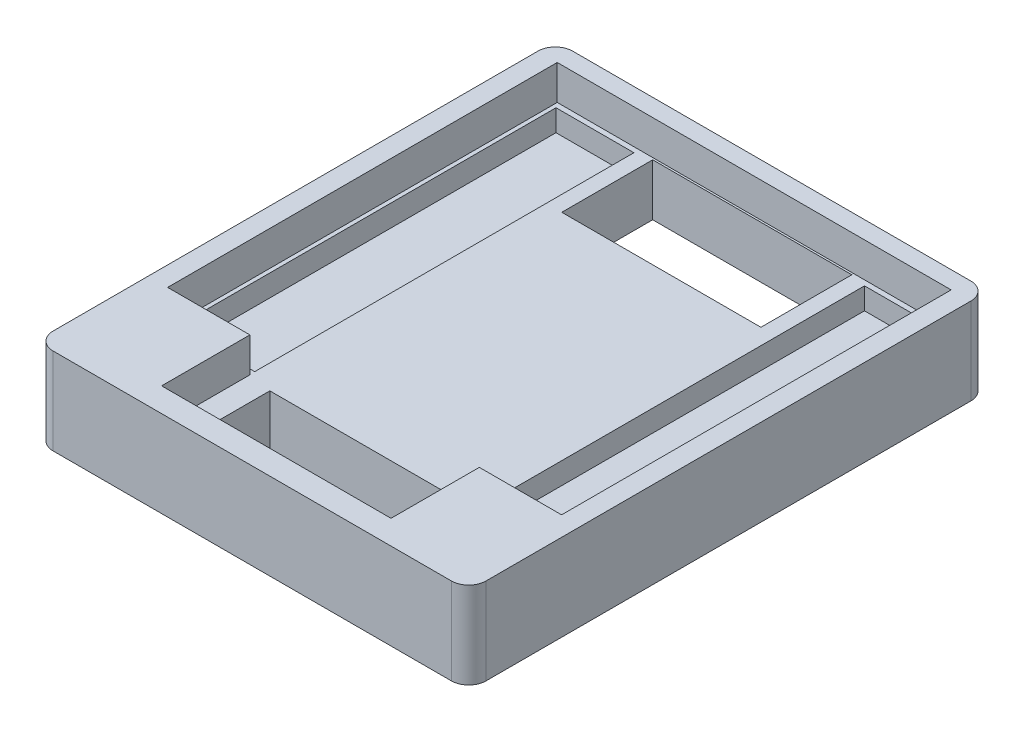
SolidWorks part; units mm, degrees
ref_plane "Front Plane" through (0, 0, 0) normal (0, 0, 1) x (1, 0, 0)
ref_plane "Top Plane" through (0, 0, 0) normal (0, 1, 0) x (1, 0, 0)
ref_plane "Right Plane" through (0, 0, 0) normal (1, 0, 0) x (0, 0, -1)
sketch "Sketch1" plane through (0, 0, 0) normal (0, 1, 0) x (1, 0, 0)
  line L1 (-25, 30) -> (25, 30)
  line L2 (-25, 30) -> (-25, -30)
  line L3 (-25, -30) -> (25, -30)
  line L4 (25, 30) -> (25, -30)
  line L5 (-25, 30) -> (25, -30) construction
  line L6 (-25, -30) -> (25, 30) construction
  point P0 (0, 0)
  dimension "D1" = 60
  dimension "D2" = 50
extrude "Boss-Extrude1" add sketch "Sketch1" along normal blind 10
sketch "Sketch2" plane through (0, 10, 0) normal (0, 1, 0) x (1, 0, 0)
  line L0 (-13.25, -22.1225) -> (-12.75, -22.1225) construction
  line L1 (-22.75, 27.975) -> (22.75, 27.975)
  line L2 (-22.75, 27.975) -> (-22.75, -17.025)
  line L3 (-22.75, -17.025) -> (-13.25, -17.025)
  line L4 (22.75, 27.975) -> (22.75, -17.025)
  line L5 (-22.75, 27.975) -> (22.75, -17.025) construction
  line L6 (-22.75, -17.025) -> (22.75, 27.975) construction
  line L7 (13.25, -17.025) -> (22.75, -17.025)
  line L8 (-13.25, -17.025) -> (-13.25, -27.22)
  line L9 (-13.25, -27.22) -> (13.25, -27.22)
  line L10 (13.25, -17.025) -> (13.25, -27.22)
  line L11 (-12.75, -16.72) -> (-12.75, -26.72) construction
  line L12 (-12.75, -22.1225) -> (12.75, -22.1225) construction
  line L13 (12.75, -26.72) -> (12.75, -16.72) construction
  line L14 (12.75, -22.1225) -> (13.25, -22.1225) construction
  line L15 (0, -26.72) -> (0, -27.22) construction
  line L16 (-12.75, -26.72) -> (12.75, -26.72) construction
  point P0 (0, 5.475)
  dimension "D1" = 45
  dimension "D2" = 45.5
  dimension "D3" = 0.5
  dimension "D4" = 0.5
extrude "Cut-Extrude1" cut sketch "Sketch2" against normal blind 4
sketch "Sketch3" plane through (0, 0, 0) normal (0, -1, 0) x (1, 0, 0)
  line L0 (10.5, -27) -> (-10.5, -18) construction
  line L1 (-10.5, -18) -> (0, -22.5) construction
  line L2 (0, 30) -> (0, 21.72) construction
  line L3 (11.5, -27.75) -> (-11.5, -27.75)
  line L4 (11.5, -27.75) -> (11.5, -17.25)
  line L5 (11.5, -17.25) -> (-11.5, -17.25)
  line L6 (-11.5, -27.75) -> (-11.5, -17.25)
  line L7 (11.5, -27.75) -> (-11.5, -17.25) construction
  line L8 (11.5, -17.25) -> (-11.5, -27.75) construction
  line L9 (-25, 30) -> (25, 30) construction
  line L11 (10.5, 17.47) -> (-10.5, 17.47)
  line L12 (10.5, 17.47) -> (10.5, 25.97)
  line L13 (10.5, 25.97) -> (-10.5, 25.97)
  line L14 (-10.5, 17.47) -> (-10.5, 25.97)
  line L15 (10.5, 17.47) -> (-10.5, 25.97) construction
  line L16 (10.5, 25.97) -> (-10.5, 17.47) construction
  dimension "D1" = 23
  dimension "D2" = 10.5
  dimension "D3" = 8.5
extrude "Cut-Extrude2" cut sketch "Sketch3" against normal blind 10
sketch "Sketch4" plane through (0, 6, 0) normal (0, 1, 0) x (1, 0, 0)
  line L0 (-13.7721, 27) -> (-21.815, -16.05) construction
  line L1 (21.815, 27) -> (-21.815, 27) construction
  line L2 (-21.815, -16.05) -> (-17.7936, 5.475) construction
  line L3 (13.8625, 27) -> (21.815, -16.05) construction
  line L4 (-21.815, -16.05) -> (21.815, -16.05) construction
  line L5 (21.815, -16.05) -> (21.815, 27) construction
  line L6 (21.815, -16.05) -> (17.8387, 5.475) construction
  line L8 (-22.2936, 27.375) -> (-13.2936, 27.375)
  line L9 (-22.2936, 27.375) -> (-22.2936, -16.425)
  line L10 (-22.2936, -16.425) -> (-13.2936, -16.425)
  line L11 (-13.2936, 27.375) -> (-13.2936, -16.425)
  line L12 (-22.2936, 27.375) -> (-13.2936, -16.425) construction
  line L13 (-22.2936, -16.425) -> (-13.2936, 27.375) construction
  line L14 (22.3387, 27.375) -> (13.3387, 27.375)
  line L15 (22.3387, 27.375) -> (22.3387, -16.425)
  line L16 (22.3387, -16.425) -> (13.3387, -16.425)
  line L17 (13.3387, 27.375) -> (13.3387, -16.425)
  line L18 (22.3387, 27.375) -> (13.3387, -16.425) construction
  line L19 (22.3387, -16.425) -> (13.3387, 27.375) construction
  dimension "D1" = 43.8
  dimension "D2" = 9
extrude "Cut-Extrude3" cut sketch "Sketch4" against normal blind 2.5
sketch "Sketch5" plane through (0, 0, 0) normal (0, -1, 0) x (1, 0, 0)
  line L1 (17.5, -15.5) -> (-17.5, -15.5)
  line L2 (17.5, -15.5) -> (17.5, 3.5)
  line L3 (17.5, 3.5) -> (-17.5, 3.5)
  line L4 (-17.5, -15.5) -> (-17.5, 3.5)
  line L5 (17.5, -15.5) -> (-17.5, 3.5) construction
  line L6 (17.5, 3.5) -> (-17.5, -15.5) construction
  point P0 (0, -6)
  dimension "D1" = 19
  dimension "D2" = 35
extrude "Cut-Extrude4" cut sketch "Sketch5" against normal blind 1.5
sketch "Sketch6" plane through (0, 0, 0) normal (0, -1, 0) x (1, 0, 0)
  line L1 (6.15, 6.6) -> (-6.15, 6.6)
  line L2 (6.15, 6.6) -> (6.15, 13.4)
  line L3 (6.15, 13.4) -> (-6.15, 13.4)
  line L4 (-6.15, 6.6) -> (-6.15, 13.4)
  line L5 (6.15, 6.6) -> (-6.15, 13.4) construction
  line L6 (6.15, 13.4) -> (-6.15, 6.6) construction
  point P0 (0, 10)
  dimension "D1" = 6.8
  dimension "D2" = 12.3
extrude "Cut-Extrude5" cut sketch "Sketch6" against normal blind 1.5
fillet "Fillet1" radius 2 4 edges at (-25, 5, -30) (-25, 5, 30) (25, 5, 30) (25, 5, -30)
